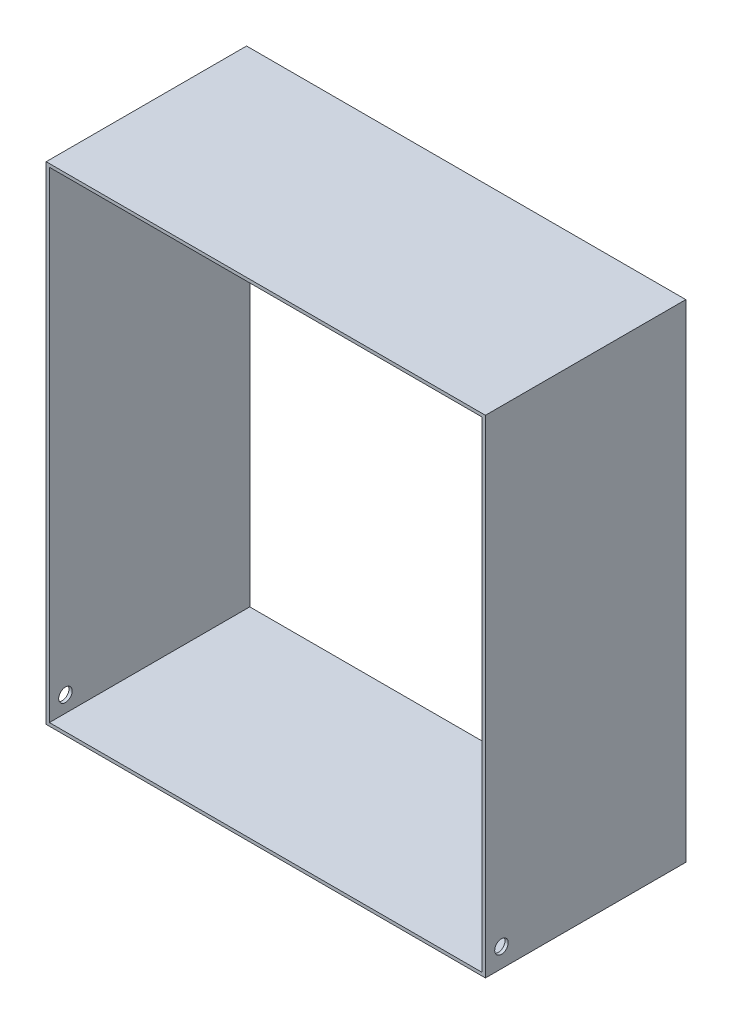
SolidWorks part; units mm, degrees
ref_plane "Front Plane" through (0, 0, 0) normal (0, 0, 1) x (1, 0, 0)
ref_plane "Top Plane" through (0, 0, 0) normal (0, 1, 0) x (1, 0, 0)
ref_plane "Right Plane" through (0, 0, 0) normal (1, 0, 0) x (0, 0, -1)
sketch "Sketch1" plane through (0, 0, 0) normal (0, 0, 1) x (1, 0, 0)
  line L0 (270, 302) -> (272, 302)
  line L1 (0, 0) -> (270, 0)
  line L2 (0, 0) -> (0, 300)
  line L3 (0, 300) -> (270, 300)
  line L4 (270, 0) -> (270, 300)
  line L5 (-2, 300) -> (-2, 0)
  line L6 (272, 302) -> (272, 300)
  line L7 (0, -2) -> (270, -2)
  line L8 (0, 302) -> (-2, 302)
  line L9 (-2, 302) -> (-2, 300)
  line L10 (272, 300) -> (272, 0)
  line L11 (0, 302) -> (270, 302)
  line L12 (-2, 0) -> (-2, -2)
  line L13 (-2, -2) -> (0, -2)
  line L14 (272, 0) -> (272, -2)
  line L15 (272, -2) -> (270, -2)
extrude "Boss-Extrude1" add sketch "Sketch1" against normal blind 125
sketch "Sketch5" plane through (272, 0, 0) normal (1, 0, 0) x (0, 0, -1)
  circle A0 centre (10, 10) radius 4.2
extrude "Cut-Extrude1" cut sketch "Sketch5" against normal blind 299
